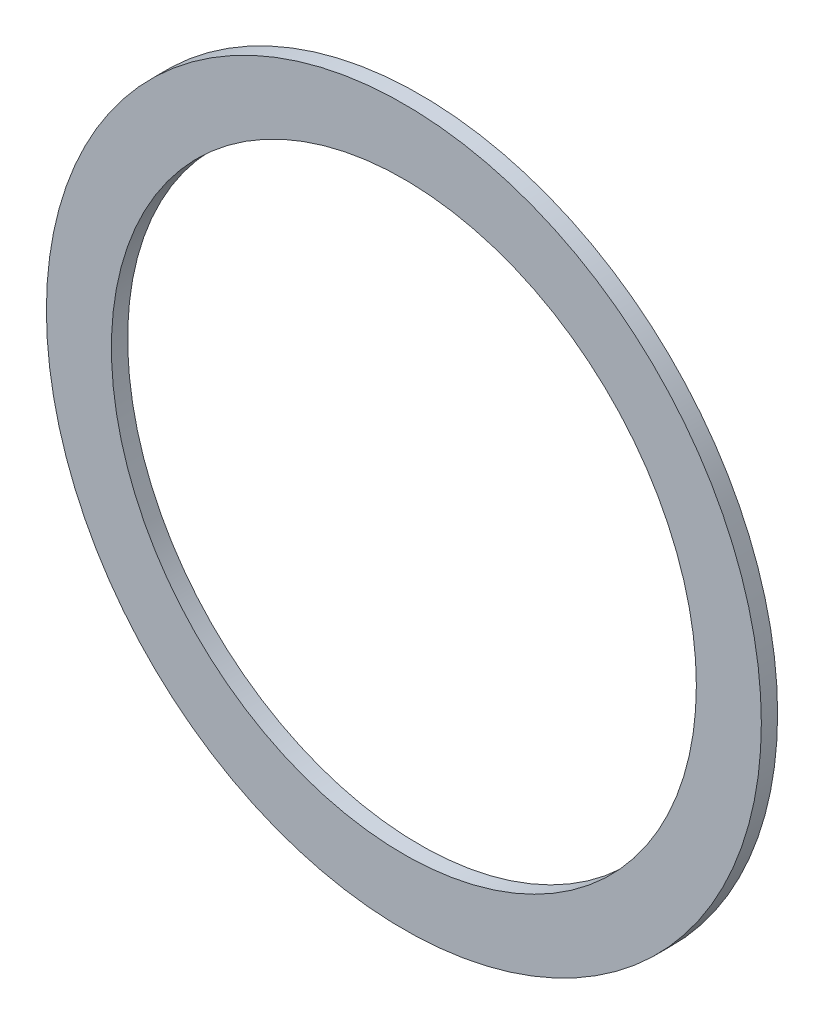
SolidWorks part; units mm, degrees
ref_plane "Ön Düzlem" through (0, 0, 0) normal (0, 0, 1) x (1, 0, 0)
ref_plane "Üst Düzlem" through (0, 0, 0) normal (0, 1, 0) x (1, 0, 0)
ref_plane "Sağ Düzlem" through (0, 0, 0) normal (1, 0, 0) x (0, 0, -1)
sketch "Çizim1" plane through (0, 0, 0) normal (0, 0, 1) x (1, 0, 0)
  circle A0 centre (0, 0) radius 9
  circle A1 centre (0, 0) radius 11
  dimension "D1" = 22
  dimension "D2" = 18
extrude "Yükseklik-Ekstrüzyon1" add sketch "Çizim1" along normal blind 0.5
